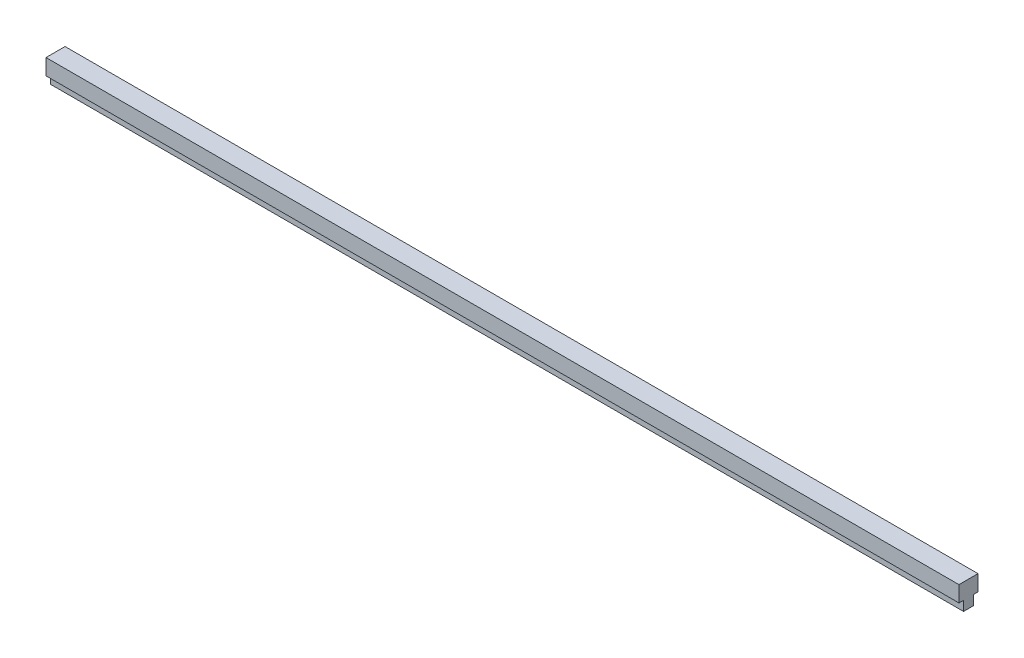
SolidWorks part; units mm, degrees
ref_plane "前视基准面" through (0, 0, 0) normal (0, 0, 1) x (1, 0, 0)
ref_plane "上视基准面" through (0, 0, 0) normal (0, 1, 0) x (1, 0, 0)
ref_plane "右视基准面" through (0, 0, 0) normal (1, 0, 0) x (0, 0, -1)
other "Configuration Table"
sketch "草图1" plane through (0, 0, 0) normal (1, 0, 0) x (0, 0, -1)
  line L0 (0, 6.1) -> (2.9, 6.1)
  line L1 (0, 0) -> (-6.2, 0)
  line L2 (0, 0) -> (0, 6.1)
  line L4 (-6.2, 0) -> (-6.2, 6.1)
  line L5 (2.9, 6.1) -> (2.9, 16.1)
  line L6 (2.9, 16.1) -> (-9.1, 16.1)
  line L7 (-9.1, 16.1) -> (-9.1, 6.1)
  line L8 (-9.1, 6.1) -> (-6.2, 6.1)
  dimension "D1" = 6.1
  dimension "D2" = 6.2
  dimension "D3" = 10
  dimension "D4" = 6.1
  dimension "D5" = 12
  dimension "D6" = 2.9
extrude "凸台-拉伸1" add sketch "草图1" along normal blind 575
